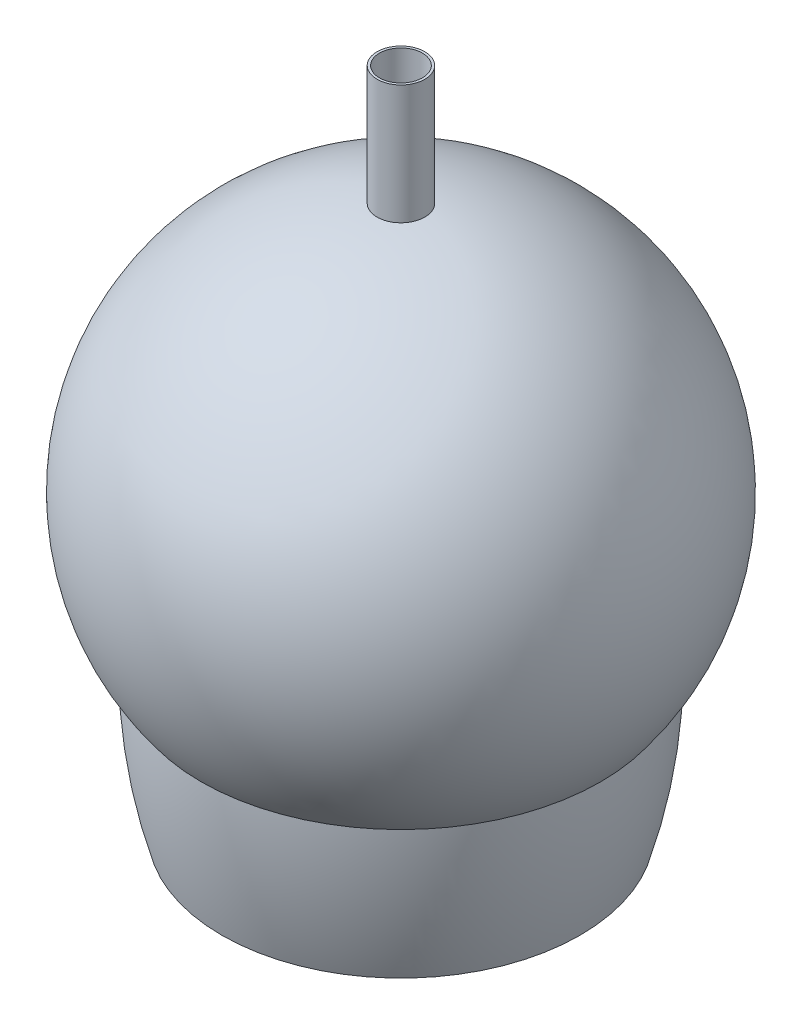
SolidWorks part; units mm, degrees
ref_plane "Front Plane" through (0, 0, 0) normal (0, 0, 1) x (1, 0, 0)
ref_plane "Top Plane" through (0, 0, 0) normal (0, 1, 0) x (1, 0, 0)
ref_plane "Right Plane" through (0, 0, 0) normal (1, 0, 0) x (0, 0, -1)
sketch "Sketch1" plane through (0, 0, 0) normal (0, 0, 1) x (1, 0, 0)
  line L0 (0, 0) -> (0, 123.4438) construction
  line L1 (0, 0) -> (-75, 0)
  line L2 (-10, 227.9665) -> (-10, 277.9665)
  arc A0 (-75, 0) -> (-83.6653, 60) centre (133.4942, 60.7368) cw
  arc A1 (-83.6653, 60) -> (-10, 227.9665) centre (0, 123.4438) cw
  point P6 (0, 0)
  point P9 (-106.6169, 124.1877)
  point P10 (-22.9251, 298.3906)
  point P11 (-75, 0)
  point P12 (-83.6791, 60.78)
  point P13 (-10.5263, 248.1755)
  point P14 (0, 0)
  dimension "D2" = 60
  dimension "D6" = 217.1607
  dimension "D3" = 105
  dimension "D7" = 10
  dimension "D1" = 75
  dimension "D4" = 50
  dimension "D5" = 83.6653
revolve "Revolve-Thin1" add sketch "Sketch1" angle 360 about L0
